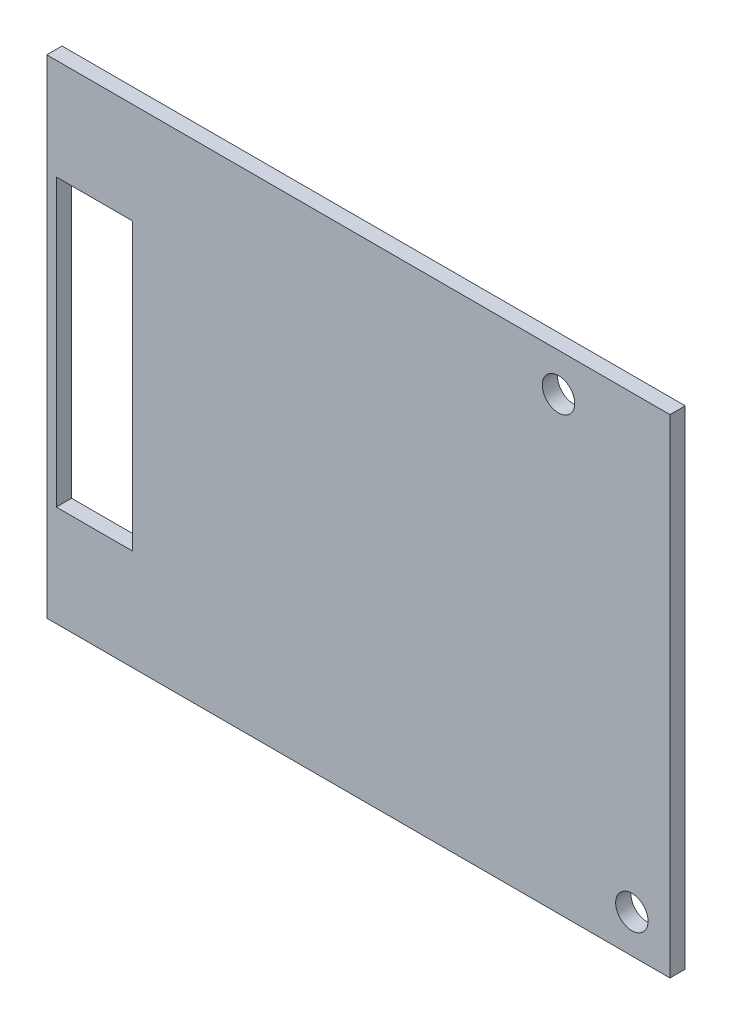
SolidWorks part; units mm, degrees
ref_plane "Front Plane" through (0, 0, 0) normal (0, 0, 1) x (1, 0, 0)
ref_plane "Top Plane" through (0, 0, 0) normal (0, 1, 0) x (1, 0, 0)
ref_plane "Right Plane" through (0, 0, 0) normal (1, 0, 0) x (0, 0, -1)
sketch "Sketch1" plane through (0, 0, 0) normal (0, 0, 1) x (1, 0, 0)
  line L5 (0, 51.2) -> (65.4, 51.2)
  line L6 (0, 51.2) -> (0, 0)
  line L7 (0, 0) -> (65.4, 0)
  line L8 (65.4, 51.2) -> (65.4, 0)
  line L9 (1, 40.6) -> (9, 40.6)
  line L14 (1, 40.6) -> (1, 10.6)
  line L15 (1, 10.6) -> (9, 10.6)
  line L16 (9, 40.6) -> (9, 10.6)
  line B0 (0, 4) -> (65.4, 4) construction
  line B1 (0, 0) -> (65.4, 0) construction
  line B2 (0, 0) -> (0, 51.2) construction
  line B3 (0, 51.2) -> (65.4, 51.2) construction
  line B4 (65.4, 0) -> (65.4, 51.2) construction
  line B5 (65.4, 47.2) -> (0, 47.2) construction
  line B6 (61.4, 51.2) -> (61.4, 0) construction
  line B7 (53.7, 51.2) -> (53.7, 0) construction
  line B8 (0, 25.6) -> (65.4, 25.6) construction
  line B9 (1, 40.6) -> (9, 40.6) construction
  line B10 (1, 40.6) -> (1, 10.6) construction
  line B11 (1, 10.6) -> (9, 10.6) construction
  line B12 (9, 40.6) -> (9, 10.6) construction
  circle B13 centre (61.4, 4) radius 1.7
  circle B14 centre (53.7, 47.2) radius 1.7
sketch_block_instance "Block1-1"
sketch_block "Block1" parameters "D4"=3.4, "D1"=51.2, "D2"=65.4, "D3"=4, "D5"=4, "D6"=11.7, "D7"=4, "D8"=30, "D9"=8, "D10"=1
extrude "Boss-Extrude1" add sketch "Sketch1" along normal blind 1.6
